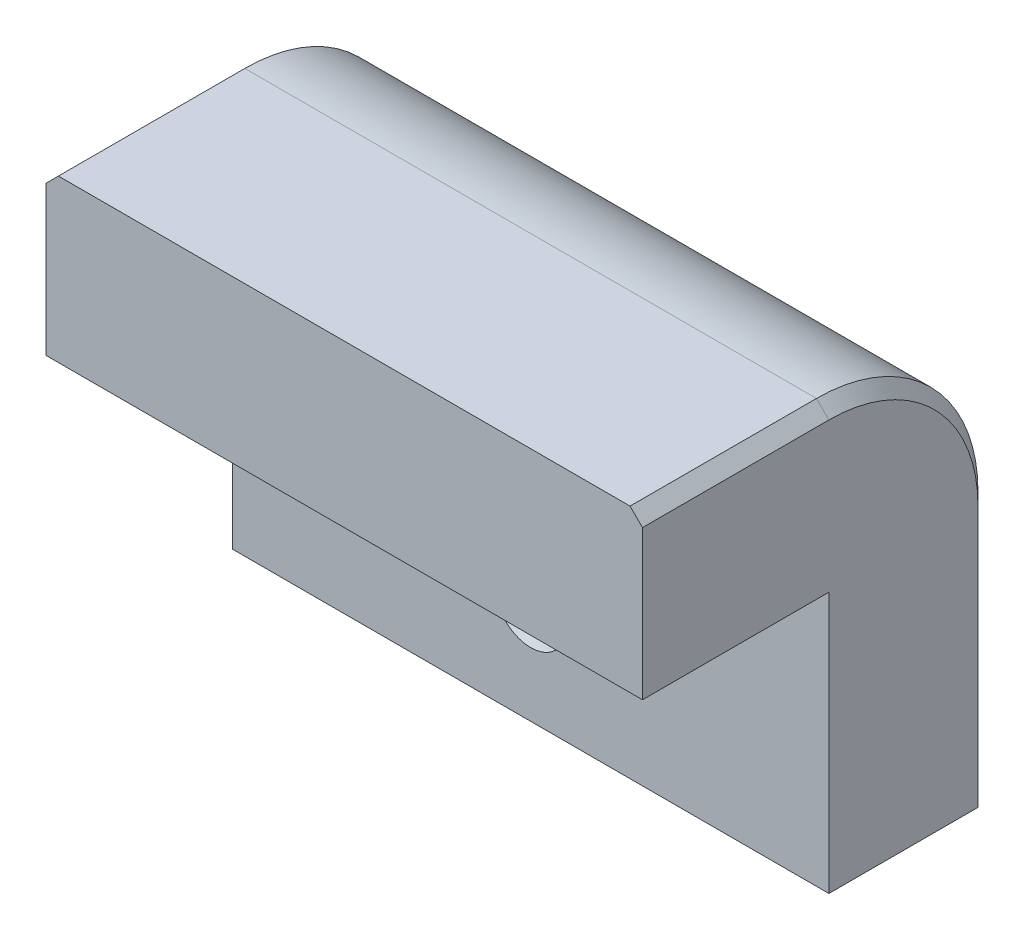
SolidWorks part; units mm, degrees
ref_plane "Front Plane" through (0, 0, 0) normal (0, 0, 1) x (1, 0, 0)
ref_plane "Top Plane" through (0, 0, 0) normal (0, 1, 0) x (1, 0, 0)
ref_plane "Right Plane" through (0, 0, 0) normal (1, 0, 0) x (0, 0, -1)
sketch "Sketch1" plane through (0, 0, 0) normal (0, 1, 0) x (1, 0, 0)
  line L0 (-30.48, 8.255) -> (30.48, 8.255)
  line L1 (-25.4, 3.175) -> (25.4, 3.175)
  line L2 (-25.4, 3.175) -> (-25.4, -3.175)
  line L3 (-25.4, -3.175) -> (25.4, -3.175)
  line L4 (25.4, 3.175) -> (25.4, -3.175)
  line L5 (-25.4, 3.175) -> (25.4, -3.175) construction
  line L6 (-25.4, -3.175) -> (25.4, 3.175) construction
  line L7 (30.48, 8.255) -> (30.48, -8.255)
  line L8 (-30.48, -8.255) -> (30.48, -8.255)
  line L9 (-30.48, 8.255) -> (-30.48, -8.255)
  point P0 (0, 0)
  dimension "D1" = 50.8
  dimension "D2" = 6.35
  dimension "D3" = 5.08
extrude "Boss-Extrude1" add sketch "Sketch1" along normal blind 19.05
sketch "Sketch5" plane through (30.48, 0, 0) normal (1, 0, 0) x (0, 0, -1)
  line L0 (-13.4061, 19.05) -> (12.4649, 19.05) construction
  line L2 (-8.255, 35.56) -> (-27.305, 35.56)
  line L3 (-27.305, 35.56) -> (-27.305, 19.05)
  line L4 (-8.255, 19.05) -> (-27.305, 19.05)
  line L5 (-8.255, 15.823) -> (-8.255, 19.05) construction
  line L6 (-8.255, 19.05) -> (-8.255, 0) construction
  line L7 (8.255, 19.05) -> (-8.255, 19.05)
  arc A0 (8.255, 19.05) -> (-8.255, 35.56) centre (-8.255, 19.05) ccw
extrude "Boss-Extrude2" add sketch "Sketch5" against normal up to surface (60.96 mm away) up to face at (-30.48, 9.525, 0)
sketch "Sketch6" plane through (0, 0, 0) normal (0, -1, 0) x (1, 0, 0)
  line L1 (-30.48, 8.255) -> (30.48, 8.255)
  line L2 (-30.48, 8.255) -> (-30.48, -8.255)
  line L3 (-30.48, -8.255) -> (30.48, -8.255)
  line L4 (30.48, 8.255) -> (30.48, -8.255)
  line L5 (25.4, 3.175) -> (-25.4, 3.175)
  line L6 (25.4, 3.175) -> (25.4, -3.175)
  line L7 (25.4, -3.175) -> (-25.4, -3.175)
  line L8 (-25.4, 3.175) -> (-25.4, -3.175)
extrude "Boss-Extrude3" add sketch "Sketch6" along normal blind 7.62
sketch "Sketch7" plane through (0, 19.05, 0) normal (0, -1, 0) x (1, 0, 0)
  line L1 (-25.4, 3.175) -> (25.4, 3.175)
  line L2 (-25.4, 3.175) -> (-25.4, -3.175)
  line L3 (-25.4, -3.175) -> (25.4, -3.175)
  line L4 (25.4, 3.175) -> (25.4, -3.175)
extrude "Boss-Extrude4" add sketch "Sketch7" along normal blind 7.62
sketch "Sketch9" plane through (0, 0, 8.255) normal (0, 0, 1) x (1, 0, 0)
  circle A0 centre (0, 2.54) radius 1.524
  dimension "D1" = 3.048
extrude "Cut-Extrude1" cut sketch "Sketch9" against normal through all
chamfer "Chamfer1" distance 2.1082 angle 41 1 edges at (1.524, 2.54, 8.255)
sketch "Sketch11" plane through (0, -7.62, 0) normal (0, -1, 0) x (1, 0, 0)
  line L16 (26.035, -3.81) -> (26.035, 3.81)
  line L17 (-26.035, -3.81) -> (26.035, -3.81)
  line L18 (-26.035, 3.81) -> (-26.035, -3.81)
  line L19 (26.035, 3.81) -> (-26.035, 3.81)
  line L20 (26.035, -3.81) -> (26.035, 3.81)
  line L21 (-26.035, -3.81) -> (26.035, -3.81)
  line L22 (-26.035, 3.81) -> (-26.035, -3.81)
  line L23 (26.035, 3.81) -> (-26.035, 3.81)
  dimension "D1" = 0.635
extrude "Cut-Extrude2" cut sketch "Sketch11" against normal blind 19.05
chamfer "Chamfer2" distance 1.27 angle 45 6 edges at (30.48, 5.715, -8.255) (-30.48, 35.56, 17.78) (30.48, 35.56, 17.78) (-30.48, 30.7243, -3.4193) (30.48, 30.7243, -3.4193) (-30.48, 5.715, -8.255)
